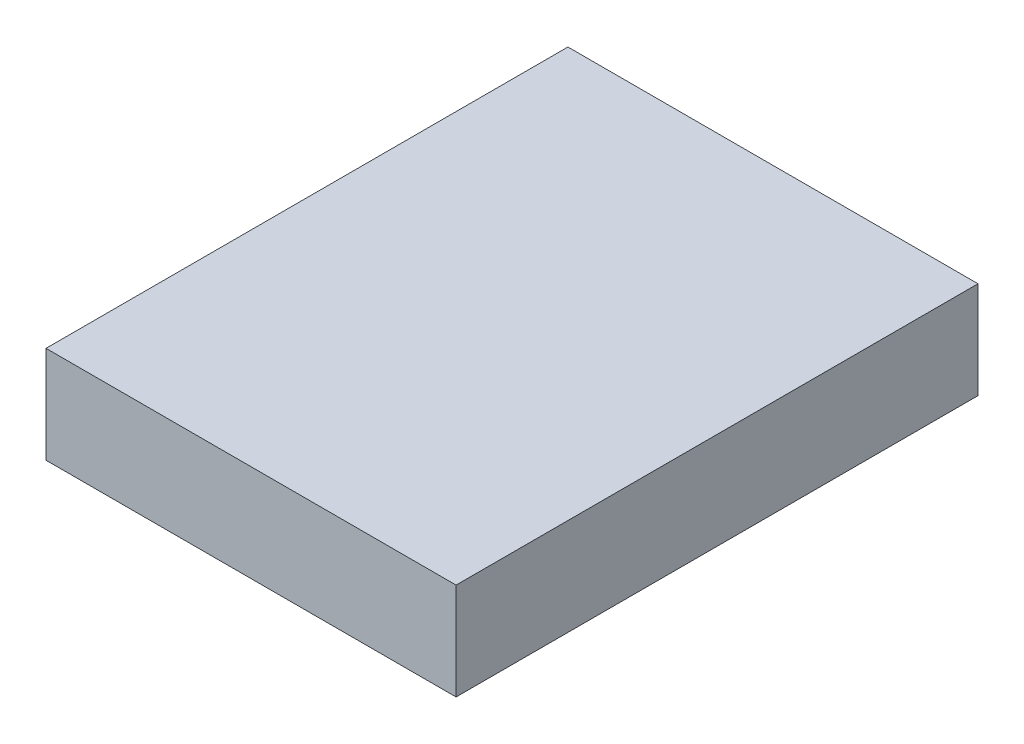
SolidWorks part; units mm, degrees
ref_plane "Front Plane" through (0, 0, 0) normal (0, 0, 1) x (1, 0, 0)
ref_plane "Top Plane" through (0, 0, 0) normal (0, 1, 0) x (1, 0, 0)
ref_plane "Right Plane" through (0, 0, 0) normal (1, 0, 0) x (0, 0, -1)
sketch "Sketch1" plane through (0, 0, 0) normal (0, 1, 0) x (1, 0, 0)
  line L1 (29.9875, 33.9718) -> (-25.0125, 33.9718)
  line L2 (29.9875, 33.9718) -> (29.9875, -36.0282)
  line L3 (29.9875, -36.0282) -> (-25.0125, -36.0282)
  line L4 (-25.0125, 33.9718) -> (-25.0125, -36.0282)
  dimension "D1" = 70
  dimension "D2" = 55
extrude "Boss-Extrude1" add sketch "Sketch1" along normal blind 13
